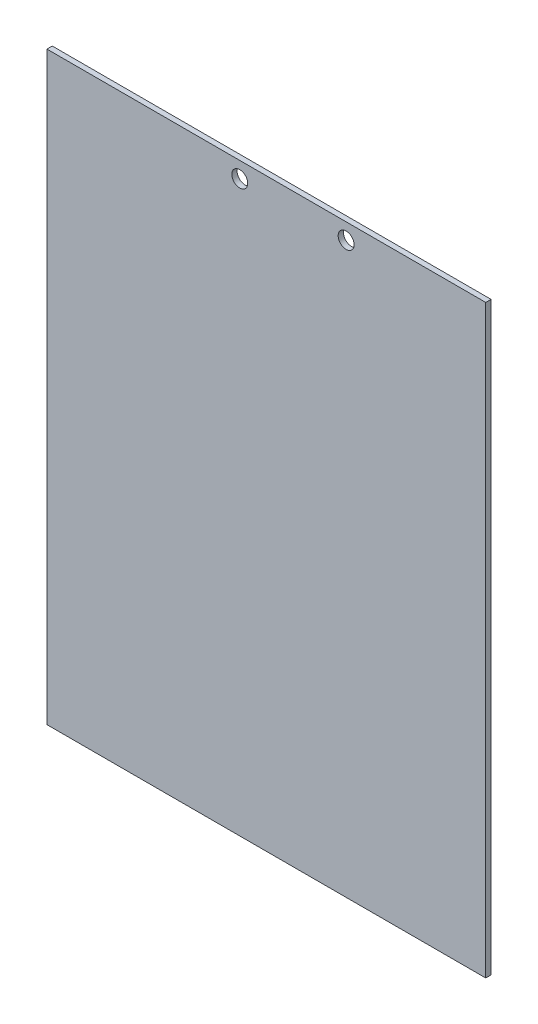
SolidWorks part; units mm, degrees
ref_plane "前视基准面" through (0, 0, 0) normal (0, 0, 1) x (1, 0, 0)
ref_plane "上视基准面" through (0, 0, 0) normal (0, 1, 0) x (1, 0, 0)
ref_plane "右视基准面" through (0, 0, 0) normal (1, 0, 0) x (0, 0, -1)
sketch "草图1" plane through (0, 0, 0) normal (0, 0, 1) x (1, 0, 0)
  line L0 (41.25, 110) -> (41.25, 0) construction
  line L1 (0, 0) -> (82.5, 0)
  line L2 (0, 0) -> (0, 110)
  line L3 (0, 110) -> (82.5, 110)
  line L4 (82.5, 0) -> (82.5, 110)
  line L8 (36.25, 110) -> (36.25, 107) construction
  line L9 (36.25, 107) -> (56.25, 107) construction
  circle A0 centre (36.25, 107) radius 1.5
  circle A1 centre (56.25, 107) radius 1.5
  dimension "D3" = 3
  dimension "D1" = 82.5
  dimension "D2" = 110
  dimension "D4" = 3
  dimension "D5" = 5
  dimension "D6" = 20
extrude "凸台-拉伸1" add sketch "草图1" along normal blind 1
